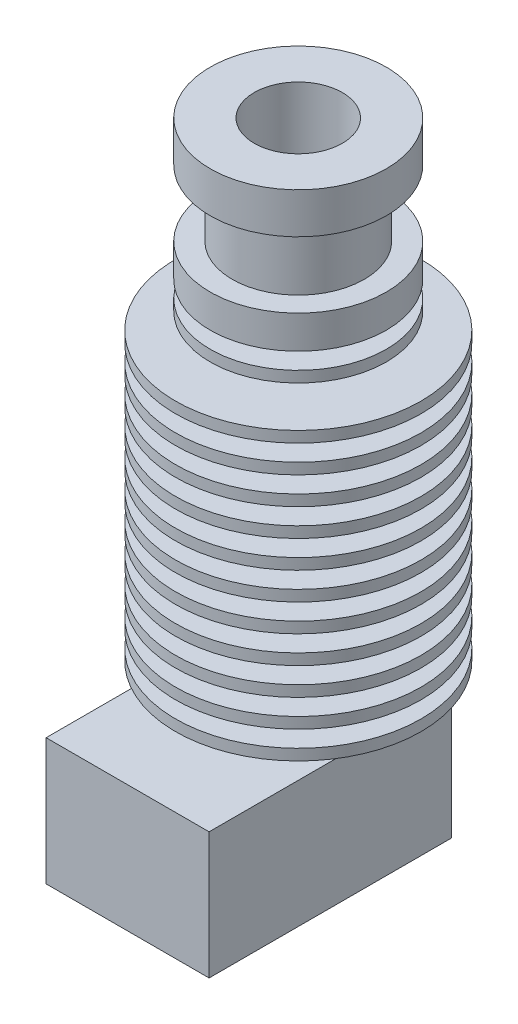
SolidWorks part; units mm, degrees
ref_plane "Front Plane" through (0, 0, 0) normal (0, 0, 1) x (1, 0, 0)
ref_plane "Top Plane" through (0, 0, 0) normal (0, 1, 0) x (1, 0, 0)
ref_plane "Right Plane" through (0, 0, 0) normal (1, 0, 0) x (0, 0, -1)
sketch "Sketch1" plane through (0, 0, 0) normal (0, 0, 1) x (1, 0, 0)
  line L0 (0, 20.5723) -> (-8, 20.5723)
  line L1 (-8, 20.5723) -> (-8, 16.8723)
  line L2 (-8, 16.8723) -> (-6, 16.8723)
  line L3 (-6, 16.8723) -> (-6, 10.8723)
  line L4 (-6, 10.8723) -> (-8, 10.8723)
  line L5 (-8, 10.8723) -> (-8, 7.8723)
  line L6 (-8, 7.8723) -> (-5.2674, 7.8723)
  line L7 (-5.2674, 7.8723) -> (-5.2674, 6.3723)
  line L8 (-5.2674, 6.3723) -> (-8, 6.3723)
  line L9 (-8, 6.3723) -> (-8, 5.3723)
  line L10 (-8, 5.3723) -> (-5.002, 5.3723)
  line L11 (-5.002, 5.3723) -> (-5.002, 3.8723)
  line L12 (-5.002, 3.8723) -> (-11.15, 3.8723)
  line L13 (-11.15, 3.8723) -> (-11.15, 2.8723)
  line L14 (-11.15, 2.8723) -> (-5.002, 2.8723)
  line L15 (-5.002, 2.8723) -> (-5.002, 1.3723)
  line L16 (-5.002, 1.3723) -> (-11.15, 1.3723)
  line L17 (-11.15, 0.3723) -> (-5.002, 0.3723)
  line L18 (-11.15, 1.3723) -> (-11.15, 0.3723)
  line L19 (-5.002, 0.3723) -> (-5.002, -1.1277)
  line L20 (-5.002, -1.1277) -> (-11.15, -1.1277)
  line L21 (-11.15, -2.1277) -> (-5.002, -2.1277)
  line L22 (-11.15, -1.1277) -> (-11.15, -2.1277)
  line L23 (-5.002, -2.1277) -> (-5.002, -3.6277)
  line L24 (-5.002, -3.6277) -> (-11.15, -3.6277)
  line L25 (-11.15, -4.6277) -> (-5.002, -4.6277)
  line L26 (-11.15, -3.6277) -> (-11.15, -4.6277)
  line L27 (-5.002, -4.6277) -> (-5.002, -6.1277)
  line L28 (-5.002, -6.1277) -> (-11.15, -6.1277)
  line L29 (-11.15, -7.1277) -> (-5.002, -7.1277)
  line L30 (-11.15, -6.1277) -> (-11.15, -7.1277)
  line L31 (-5.002, -7.1277) -> (-5.002, -8.6277)
  line L32 (-5.002, -8.6277) -> (-11.15, -8.6277)
  line L33 (-11.15, -9.6277) -> (-5.002, -9.6277)
  line L34 (-11.15, -8.6277) -> (-11.15, -9.6277)
  line L35 (-5.002, -9.6277) -> (-5.002, -11.1277)
  line L36 (-5.002, -11.1277) -> (-11.15, -11.1277)
  line L37 (-11.15, -12.1277) -> (-5.002, -12.1277)
  line L38 (-11.15, -11.1277) -> (-11.15, -12.1277)
  line L39 (-5.002, -12.1277) -> (-5.002, -13.6277)
  line L40 (-5.002, -13.6277) -> (-11.15, -13.6277)
  line L41 (-11.15, -14.6277) -> (-5.002, -14.6277)
  line L42 (-11.15, -13.6277) -> (-11.15, -14.6277)
  line L43 (-5.002, -14.6277) -> (-5.002, -16.1277)
  line L44 (-5.002, -16.1277) -> (-11.15, -16.1277)
  line L45 (-11.15, -17.1277) -> (-5.002, -17.1277)
  line L46 (-11.15, -16.1277) -> (-11.15, -17.1277)
  line L47 (-5.002, -17.1277) -> (-5.002, -18.6277)
  line L48 (-5.002, -18.6277) -> (-11.15, -18.6277)
  line L49 (-11.15, -19.6277) -> (-5.002, -19.6277)
  line L50 (-11.15, -18.6277) -> (-11.15, -19.6277)
  line L51 (-5.002, -19.6277) -> (-5.002, -21.1277)
  line L52 (-5.002, -21.1277) -> (-11.15, -21.1277)
  line L53 (-11.15, -22.1277) -> (-5.002, -22.1277)
  line L54 (-11.15, -21.1277) -> (-11.15, -22.1277)
  line L55 (-5.002, -22.1277) -> (-3, -22.1277)
  line L56 (0, 0) -> (0, 20.5723) construction
  line L57 (-3, -22.1277) -> (-3, -39.7141)
  line L58 (-0.7383, -41.6277) -> (0, -41.6277)
  line L59 (0, 20.5723) -> (0, -33.8056)
  line L60 (0, -41.6277) -> (0, -33.8056)
  line L61 (-0.7383, -41.6277) -> (-3, -39.7141)
  dimension "D1" = 1
  dimension "D2" = 2.5
  dimension "D3" = 11
  dimension "D4" = 1
  dimension "D5" = 1.5
  dimension "D6" = 3
  dimension "D7" = 6
  dimension "D8" = 3.7
  dimension "D9" = 8
  dimension "D10" = 12
  dimension "D11" = 22.3
  dimension "D13" = 0
revolve "Revolve1" add sketch "Sketch1" angle 360 about L56
sketch "Sketch2" plane through (0, 20.5723, 0) normal (0, 1, 0) x (1, 0, 0)
  circle A0 centre (0, 0) radius 4
  dimension "D1" = 8
extrude "Cut-Extrude1" cut sketch "Sketch2" against normal blind 6.5
ref_plane "Plane1" through (0, -24.1277, 0) normal (0, -1, 0) x (-1, 0, 0)
sketch "Sketch3" plane through (0, -24.1277, 0) normal (0, -1, 0) x (-1, 0, 0)
  line L1 (7.4017, 6.5) -> (-7.4017, 6.5)
  line L2 (7.4017, 6.5) -> (7.4017, -15.5)
  line L3 (7.4017, -15.5) -> (-7.4017, -15.5)
  line L4 (-7.4017, 6.5) -> (-7.4017, -15.5)
  circle A0 centre (0, 0) radius 0.7383 construction
  point P4 (0, 6.5)
  dimension "D1" = 0
  dimension "D2" = 15.5
  dimension "D3" = 22
extrude "Boss-Extrude1" add sketch "Sketch3" along normal blind 11.5
sketch "Sketch4" plane through (0, -35.6277, 0) normal (0, -1, 0) x (-1, 0, 0)
  line L1 (4.7306, 0) -> (2.3653, 4.0968)
  line L2 (2.3653, 4.0968) -> (-2.3653, 4.0968)
  line L3 (-2.3653, 4.0968) -> (-4.7306, 0)
  line L4 (-4.7306, 0) -> (-2.3653, -4.0968)
  line L5 (-2.3653, -4.0968) -> (2.3653, -4.0968)
  line L6 (2.3653, -4.0968) -> (4.7306, 0)
  circle A0 centre (0, 0) radius 4.0968 construction
extrude "Boss-Extrude2" add sketch "Sketch4" along normal blind 2
